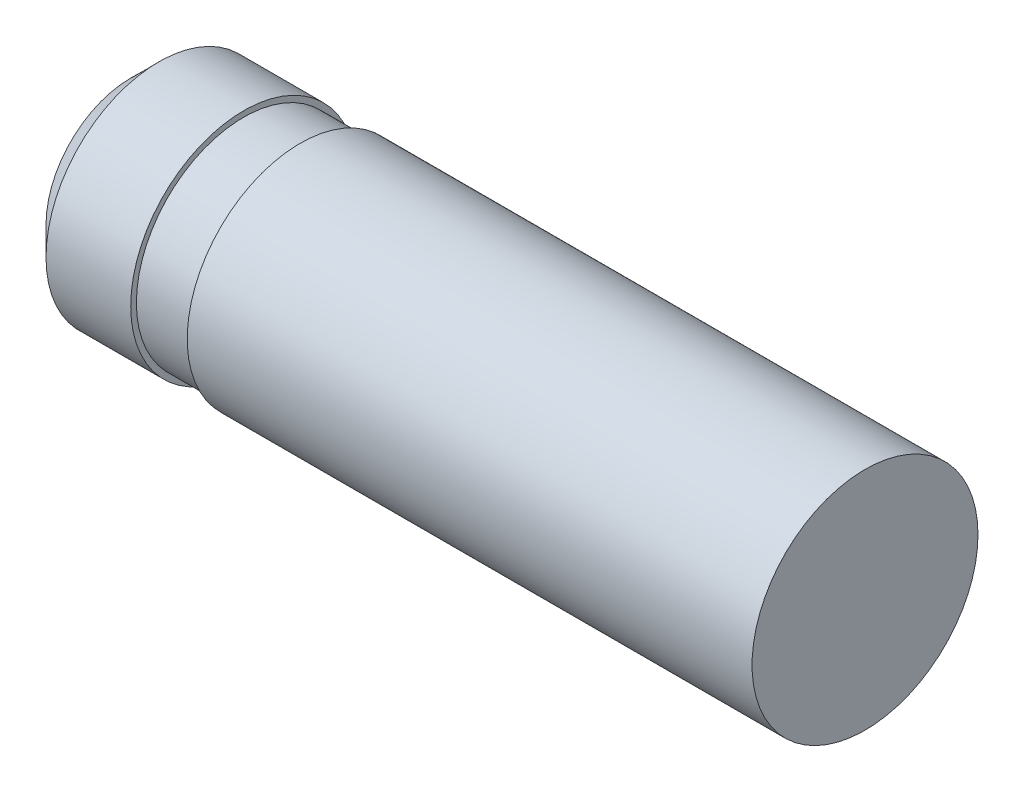
SolidWorks part; units mm, degrees
ref_plane "Front Plane" through (0, 0, 0) normal (0, 0, 1) x (1, 0, 0)
ref_plane "Top Plane" through (0, 0, 0) normal (0, 1, 0) x (1, 0, 0)
ref_plane "Right Plane" through (0, 0, 0) normal (1, 0, 0) x (0, 0, -1)
sketch "Sketch1" plane through (0, 0, 0) normal (1, 0, 0) x (0, 0, -1)
  circle A0 centre (0, 0) radius 2
  dimension "D1" = 4
extrude "Boss-Extrude2" add sketch "Sketch1" against normal blind 10
sketch "Sketch3" plane through (-10, 0, 0) normal (-1, 0, 0) x (0, 0, 1)
  circle A0 centre (0, 0) radius 1.9
  dimension "D1" = 3.8
extrude "Boss-Extrude3" add sketch "Sketch3" along normal blind 1
sketch "Sketch4" plane through (-11, 0, 0) normal (-1, 0, 0) x (0, 0, 1)
  circle A0 centre (0, 0) radius 2
  dimension "D1" = 4
extrude "Boss-Extrude4" add sketch "Sketch4" along normal blind 2
chamfer "Chamfer2" distance 0.5 angle 45 1 edges at (-13, 0, 2)
